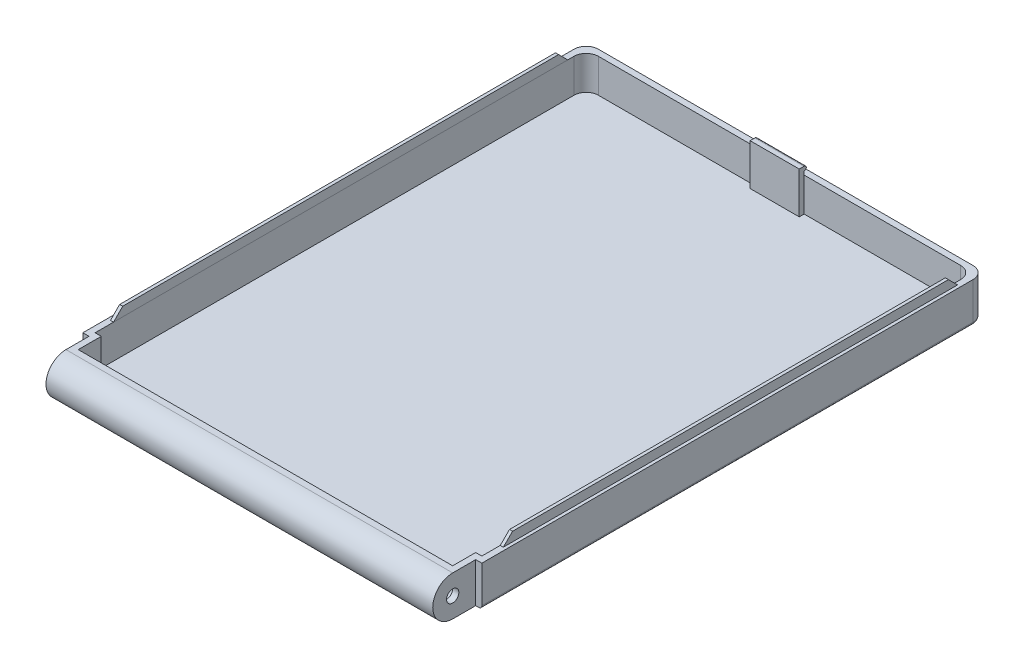
SolidWorks part; units mm, degrees
ref_plane "Alzado" through (0, 0, 0) normal (0, 0, 1) x (1, 0, 0)
ref_plane "Planta" through (0, 0, 0) normal (0, 1, 0) x (1, 0, 0)
ref_plane "Vista lateral" through (0, 0, 0) normal (1, 0, 0) x (0, 0, -1)
sketch "Croquis1" plane through (0, 0, 0) normal (0, 1, 0) x (1, 0, 0)
  line L0 (130, 0) -> (128, 0)
  line L1 (0, 0) -> (2, 0)
  line L2 (0, 0) -> (0, 160)
  line L3 (4, 164) -> (126, 164)
  line L4 (130, 0) -> (130, 160)
  line L5 (128, 0) -> (128, -14)
  line L6 (128, -14) -> (2, -14)
  line L7 (2, -14) -> (2, 0)
  arc A0 (4, 164) -> (0, 160) centre (4, 160) ccw
  arc A1 (126, 164) -> (130, 160) centre (126, 160) cw
extrude "Saliente-Extruir1" add sketch "Croquis1" along normal blind 13
sketch "Croquis7" plane through (0, 13, 0) normal (0, 1, 0) x (1, 0, 0)
  line L0 (2, 0) -> (128, 0)
  line L8 (62.0012, 162) -> (6, 162)
  line L9 (2, 158) -> (2, 2)
  line L10 (2, 2) -> (128, 2)
  line L11 (128, 2) -> (128, 158)
  line L12 (124, 162) -> (62.0012, 162)
  arc A0 (6, 162) -> (2, 158) centre (6, 158) ccw
  arc A1 (124, 162) -> (128, 158) centre (124, 158) cw
extrude "Cortar-Extruir7" cut sketch "Croquis7" against normal blind 11 contours A1 L12 L8 A0 L9 L10 L11
sketch "Croquis8" plane through (128, 0, 0) normal (1, 0, 0) x (0, 0, -1)
  line L0 (-7.5, 28.0923) -> (-7.5, -27.9424)
  line L2 (-14, 13) -> (0, 13) construction
  line L3 (-7.5, 13) -> (-7.5, 0)
  arc A0 (-7.5, 13) -> (-7.5, 0) centre (-7.5, 6.5) ccw
  line M3 (-14, 0) -> (0, 0)
  line M5 (0, 13) -> (-14, 13)
  line M6 (-14, 13) -> (-14, 0)
extrude "Cortar-Extruir9" cut sketch "Croquis8" against normal blind 140 contours A0 M5 M6 | A0 M6 M3
ref_plane "Plano1" through (4, 0, 0) normal (1, 0, 0) x (0, 0, -1)
sketch "Croquis10" plane through (4, 0, 0) normal (1, 0, 0) x (0, 0, -1)
  circle A0 centre (-7.5, 6.5) radius 4.5
extrude "Cortar-Extruir10" cut sketch "Croquis10" along normal blind 122
sketch "Croquis11" plane through (0, 13, 0) normal (0, 1, 0) x (1, 0, 0)
  line L1 (4, -5.5) -> (4, 14.525)
  line L4 (4, -5.5) -> (6, -5.5)
  line L5 (4, -7.15) -> (4, 7.15) construction
  line L6 (126, -5.5) -> (126, 14.525)
  line L9 (126, -5.5) -> (4, -5.5)
  line L10 (126, 14.525) -> (4, 14.525)
  line M4 (128, 2) -> (2, 2)
extrude "Cortar-Extruir12" cut sketch "Croquis11" against normal blind 11 contours L9 L6 L1 L4 M4 | L6 L10 L1 M4
sketch "Croquis12" plane through (4, 0, 0) normal (1, 0, 0) x (0, 0, -1)
  circle A0 centre (-7.5, 6.5) radius 2
extrude "Cortar-Extruir13" cut sketch "Croquis12" against normal blind 130 and the other way blind 130
sketch "Croquis13" plane through (0, 0, -162) normal (0, 0, 1) x (1, 0, 0)
  line L0 (124, 2) -> (6, 2) construction
  line L2 (57, 2) -> (57, 15.5)
  line L3 (57, 15.5) -> (73, 15.5)
  line L4 (73, 2) -> (73, 15.5)
  line L7 (57, 2) -> (73, 2)
  point P0 (65, 2)
extrude "Saliente-Extruir3" add sketch "Croquis13" along normal blind 1.6 separate body
sketch "Croquis14" plane through (73, 0, 0) normal (1, 0, 0) x (0, 0, -1)
  line L0 (162, 14.0959) -> (161.9237, 15.5)
  line L1 (160.4, 15.5) -> (162, 15.5) construction
  line L2 (162, 2) -> (162, 15.5) construction
  arc A0 (162, 14.0959) -> (161.9237, 15.5) centre (162, 14.8) ccw
extrude "Saliente-Extruir4" add sketch "Croquis14" against normal blind 16
fillet "Redondeo1" radius 1 5 edges at (130, 0, -80) (128.8284, 0, -162.8284) (65, 0, -164) (1.1716, 0, -162.8284) (0, 0, -80)
ref_plane "Plano2" through (2, 0, 0) normal (1, 0, 0) x (0, 0, -1)
sketch "Croquis15" plane through (2, 0, 0) normal (1, 0, 0) x (0, 0, -1)
  line L5 (160, 13) -> (0, 13) construction
  line L6 (153, 16) -> (11, 16)
  line L8 (8, 13) -> (156, 13)
  line L9 (156, 13) -> (153, 16)
  line L10 (8, 13) -> (11, 16)
extrude "Saliente-Extruir5" add sketch "Croquis15" against normal blind 1 separate body
ref_plane "Plano3" through (128, 0, 0) normal (1, 0, 0) x (0, 0, -1)
sketch "Croquis16" plane through (128, 0, 0) normal (1, 0, 0) x (0, 0, -1)
  line L0 (156, 13) -> (153, 16)
  line L1 (153, 16) -> (11, 16)
  line L2 (11, 16) -> (8, 13)
  line L3 (160, 13) -> (0, 13) construction
  line L4 (8, 13) -> (156, 13) construction
  line L5 (8, 13) -> (156, 13)
extrude "Saliente-Extruir6" add sketch "Croquis16" along normal blind 1
